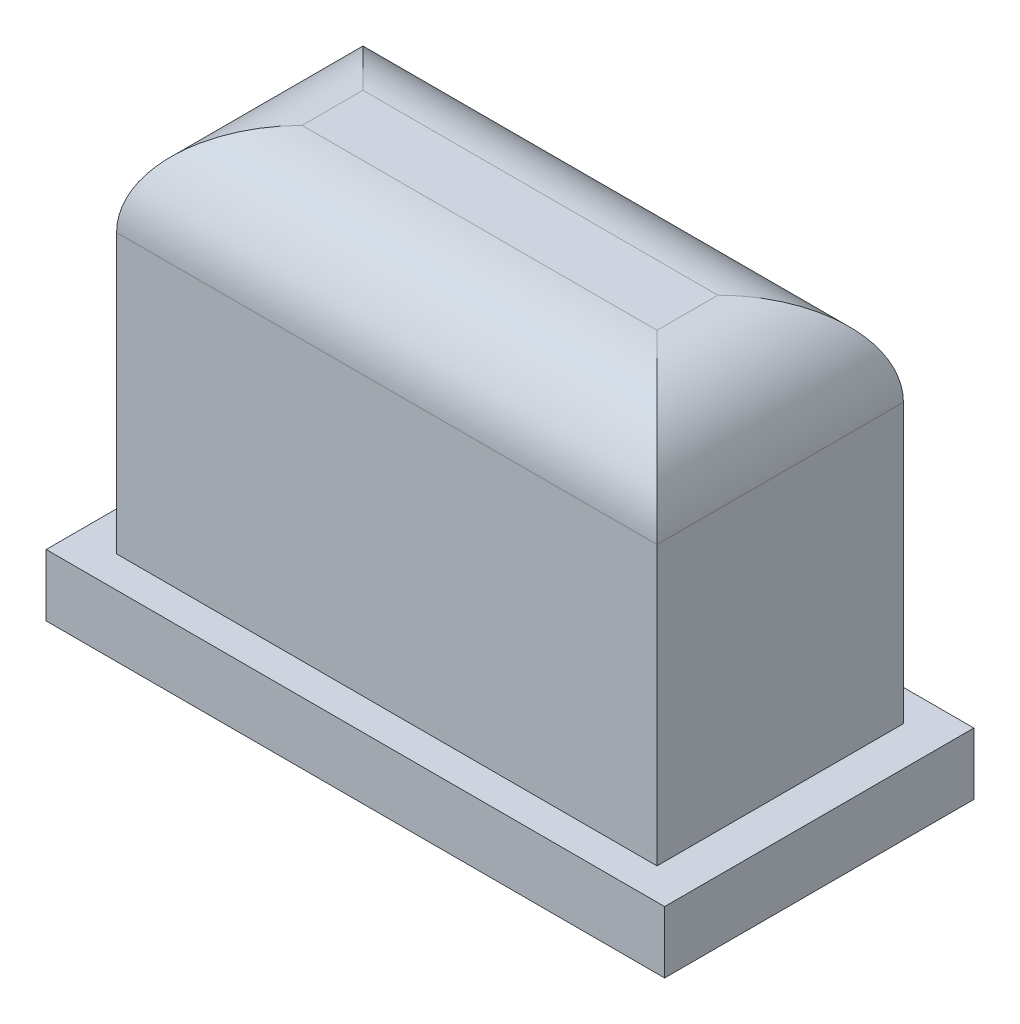
SolidWorks part; units mm, degrees
ref_plane "Alzado" through (0, 0, 0) normal (0, 0, 1) x (1, 0, 0)
ref_plane "Planta" through (0, 0, 0) normal (0, 1, 0) x (1, 0, 0)
ref_plane "Vista lateral" through (0, 0, 0) normal (1, 0, 0) x (0, 0, -1)
sketch "Croquis1" plane through (0, 0, 0) normal (0, 1, 0) x (1, 0, 0)
  line L1 (-50, -25) -> (50, -25)
  line L2 (-50, -25) -> (-50, 25)
  line L3 (-50, 25) -> (50, 25)
  line L4 (50, -25) -> (50, 25)
  line L5 (-50, -25) -> (50, 25) construction
  line L6 (-50, 25) -> (50, -25) construction
  point P0 (0, 0)
  dimension "D1" = 50
  dimension "D2" = 100
extrude "Saliente-Extruir1" add sketch "Croquis1" along normal blind 10
sketch "Croquis2" plane through (0, 10, 0) normal (0, 1, 0) x (1, 0, 0)
  line L1 (43.6902, -19.9188) -> (-43.6902, -19.9188)
  line L2 (43.6902, -19.9188) -> (43.6902, 19.9188)
  line L3 (43.6902, 19.9188) -> (-43.6902, 19.9188)
  line L4 (-43.6902, -19.9188) -> (-43.6902, 19.9188)
  line L5 (43.6902, -19.9188) -> (-43.6902, 19.9188) construction
  line L6 (43.6902, 19.9188) -> (-43.6902, -19.9188) construction
  point P0 (0, 0)
extrude "Saliente-Extruir2" add sketch "Croquis2" along normal blind 60
fillet "Redondeo1" radius 15 4 edges at (-43.6902, 70, 0) (0, 70, -19.9188) (43.6902, 70, 0) (0, 70, 19.9188)
sketch "Croquis3" plane through (0, 0, 0) normal (0, -1, 0) x (1, 0, 0)
  circle A0 centre (0, 0) radius 6.0824
extrude "Saliente-Extruir3" add sketch "Croquis3" along normal blind 10
